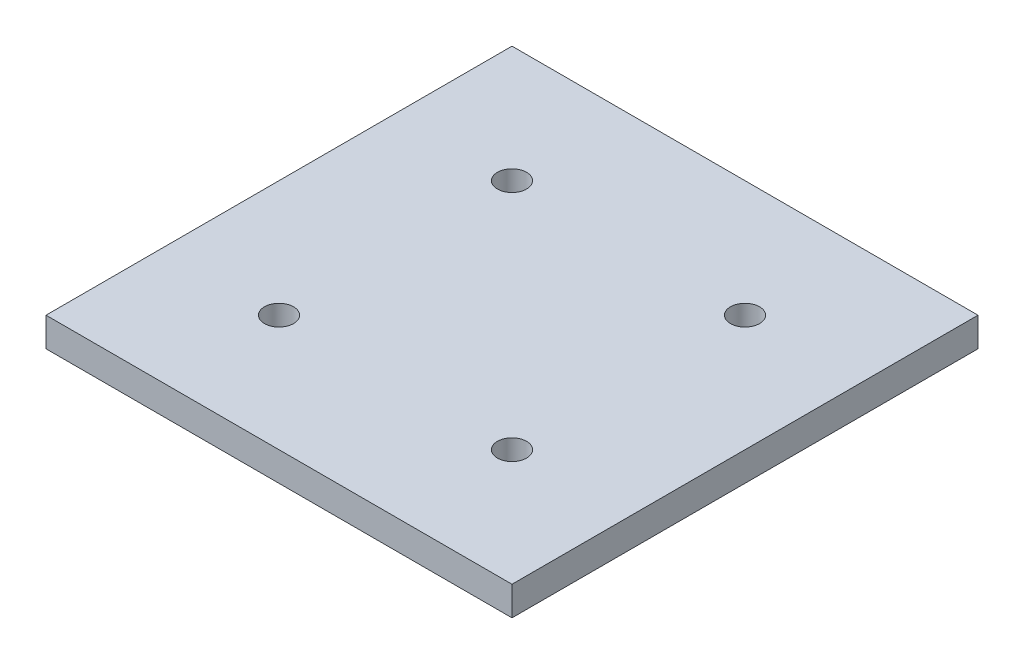
SolidWorks part; units mm, degrees
ref_plane "Front Plane" through (0, 0, 0) normal (0, 0, 1) x (1, 0, 0)
ref_plane "Top Plane" through (0, 0, 0) normal (0, 1, 0) x (1, 0, 0)
ref_plane "Right Plane" through (0, 0, 0) normal (1, 0, 0) x (0, 0, -1)
sketch "Sketch1" plane through (0, 0, 0) normal (0, 1, 0) x (1, 0, 0)
  line L0 (0, 50.8) -> (0, 0) construction
  line L1 (-50.8, 50.8) -> (50.8, 50.8)
  line L2 (-50.8, 50.8) -> (-50.8, -50.8)
  line L3 (-50.8, -50.8) -> (50.8, -50.8)
  line L4 (50.8, 50.8) -> (50.8, -50.8)
  line L5 (0, 0) -> (-50.8, 0) construction
  circle A0 centre (-25.4, 25.4) radius 3.175
  circle A1 centre (25.4, 25.4) radius 3.175
  circle A2 centre (25.4, -25.4) radius 3.175
  circle A3 centre (-25.4, -25.4) radius 3.175
  dimension "D4" = 6.35
  dimension "D1" = 101.6
  dimension "D2" = 25.4
  dimension "D3" = 25.4
extrude "Boss-Extrude2" add sketch "Sketch1" along normal blind 6.35
